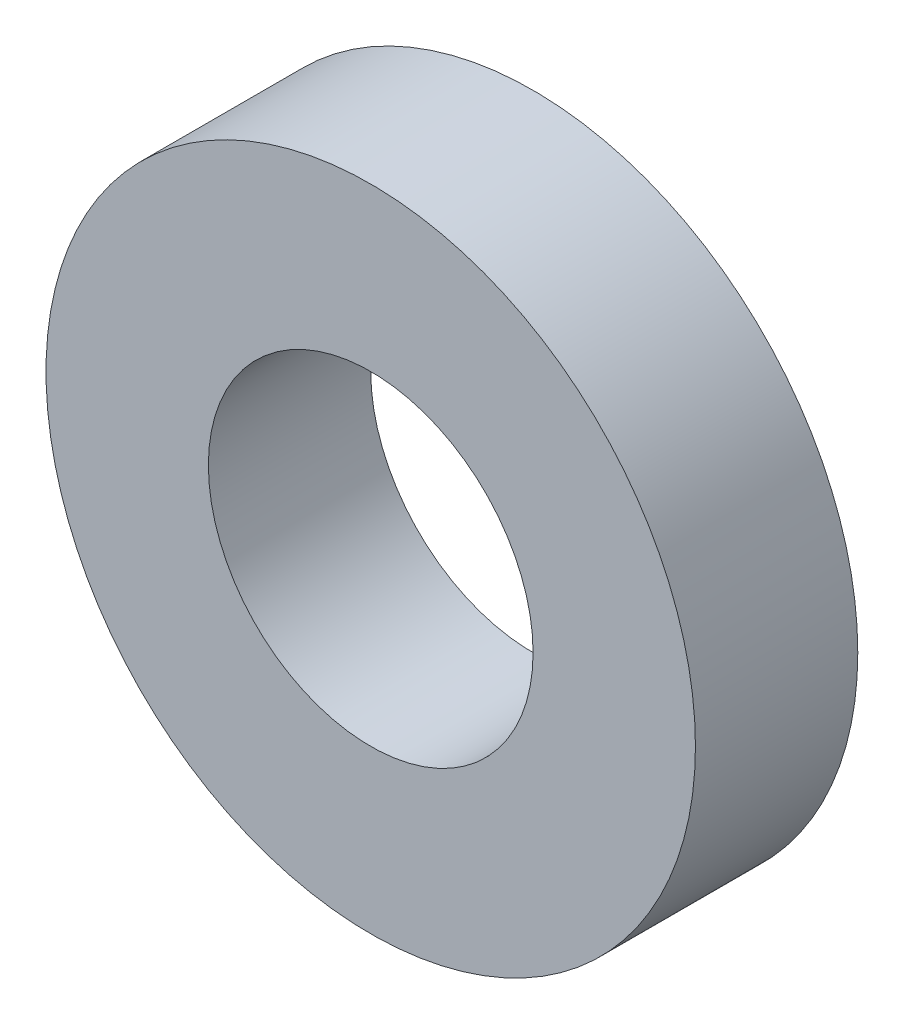
SolidWorks part; units mm, degrees
ref_plane "前视基准面" through (0, 0, 0) normal (0, 0, 1) x (1, 0, 0)
ref_plane "上视基准面" through (0, 0, 0) normal (0, 1, 0) x (1, 0, 0)
ref_plane "右视基准面" through (0, 0, 0) normal (1, 0, 0) x (0, 0, -1)
other "Configuration Table"
sketch "草图1" plane through (0, 0, 0) normal (0, 0, 1) x (1, 0, 0)
  circle A0 centre (0, 0) radius 5
  circle A1 centre (0, 0) radius 10
  dimension "D1" = 10
  dimension "D2" = 20
extrude "凸台-拉伸1" add sketch "草图1" along normal blind 5
